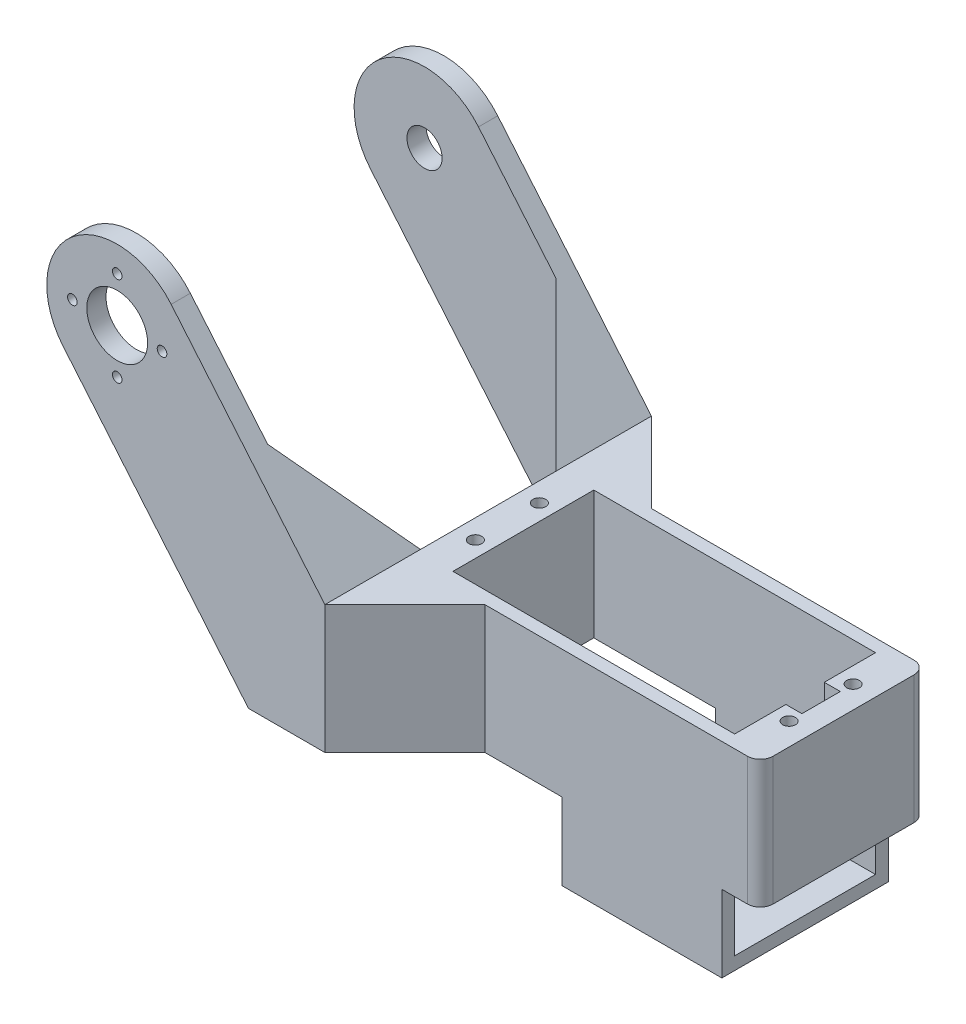
SolidWorks part; units mm, degrees
ref_plane "Alzado" through (0, 0, 0) normal (0, 0, 1) x (1, 0, 0)
ref_plane "Planta" through (0, 0, 0) normal (0, 1, 0) x (1, 0, 0)
ref_plane "Vista lateral" through (0, 0, 0) normal (1, 0, 0) x (0, 0, -1)
sketch "Croquis2" plane through (0, 0, 0) normal (0, 1, 0) x (1, 0, 0)
  line L0 (-30, 13) -> (-30, -13)
  line L1 (-22, 11) -> (22, 11)
  line L2 (-22, 11) -> (-22, -11)
  line L3 (-22, -11) -> (22, -11)
  line L4 (22, 11) -> (22, -11)
  line L5 (-22, 11) -> (22, -11) construction
  line L6 (-22, -11) -> (22, 11) construction
  line L7 (-30, -13) -> (28, -13)
  line L8 (28, 13) -> (28, -13)
  line L9 (-30, 13) -> (28, 13)
  point P0 (0, 0)
  point P10 (28, 0)
  point P11 (22, 0)
  dimension "D1" = 44
  dimension "D2" = 22
  dimension "D3" = 8
  dimension "D4" = 6
  dimension "D5" = 26
extrude "Saliente-Extruir3" add sketch "Croquis2" along normal blind 20
sketch "Croquis4" plane through (0, 20, 0) normal (0, 1, 0) x (1, 0, 0)
  line L14 (22, -11) -> (22, 11) construction
  line L15 (-22, 11) -> (-22, -11) construction
  line L16 (22, 3) -> (22, -3)
  line L17 (22, -3) -> (24.5, -3)
  line L18 (24.5, -3) -> (24.5, 3)
  line L19 (24.5, 3) -> (22, 3)
  circle A4 centre (-24.5, 5) radius 1
  circle A5 centre (-24.5, -5) radius 1
  circle A6 centre (24.5, -5) radius 1
  circle A7 centre (24.5, 5) radius 1
  point P9 (-22, 0)
  point P12 (22, 0)
  dimension "D2" = 2.5
  dimension "D1" = 2
  dimension "D3" = 10
  dimension "D4" = 2.5
  dimension "D5" = 5
  dimension "D6" = 6
  dimension "D7" = 2.5
extrude "Cut-Extrude1" cut sketch "Croquis4" against normal through all
sketch "Sketch1" plane through (-30, 0, 0) normal (-1, 0, 0) x (0, 0, 1)
  line L1 (25.5, 0) -> (-25.5, 0)
  line L2 (25.5, 0) -> (25.5, 20)
  line L3 (25.5, 20) -> (-25.5, 20)
  line L4 (-25.5, 0) -> (-25.5, 20)
  point P4 (0, 0)
  dimension "D1" = 51
extrude "Boss-Extrude1" add sketch "Sketch1" against normal blind 2.5
sketch "Croquis6" plane through (0, 0, 25.5) normal (0, 0, 1) x (1, 0, 0)
  line L0 (-27.5, 0) -> (-39.437, 0)
  line L1 (-39.437, 0) -> (-68.3624, 34.472)
  line L3 (-27.5, 20) -> (-51.5094, 48.6133)
  line L4 (-68.3624, 34.472) -> (-51.5094, 48.6133) construction
  circle A0 centre (-59.9359, 41.5427) radius 4.75
  arc A1 (-68.3624, 34.472) -> (-51.5094, 48.6133) centre (-59.9359, 41.5427) cw
  circle A3 centre (-52.9359, 41.5427) radius 0.75
  circle A4 centre (-59.9359, 34.5427) radius 0.75
  circle A5 centre (-66.9359, 41.5427) radius 0.75
  circle A6 centre (-59.9359, 48.5427) radius 0.75
  point P10 (-57.681, 41.4168)
  point P20 (-59.9359, 41.5427)
  dimension "D1" = 9.5
  dimension "D2" = 1.5
  dimension "D6" = 22
  dimension "D7" = 45
  dimension "D3" = 7
  dimension "D5" = 130
  dimension "D4" = 4
extrude "Saliente-Extruir5" add sketch "Croquis6" against normal blind 3
sketch "Sketch3" plane through (0, 0, -25.5) normal (0, 0, -1) x (-1, 0, 0)
  line L11 (51.5094, 48.6133) -> (27.5, 20)
  line L12 (27.5, 20) -> (30, 20)
  line L13 (30, 20) -> (30, 0)
  line L14 (30, 0) -> (39.437, 0)
  line L15 (39.437, 0) -> (68.3624, 34.472)
  line L16 (51.5094, 48.6133) -> (27.5, 20)
  line L17 (27.5, 20) -> (30, 20)
  line L18 (30, 20) -> (30, 0)
  line L19 (30, 0) -> (39.437, 0)
  line L20 (39.437, 0) -> (68.3624, 34.472)
  circle A3 centre (59.9359, 41.5427) radius 2.75
  arc A4 (68.3624, 34.472) -> (51.5094, 48.6133) centre (59.9359, 41.5427) ccw
  arc A9 (68.3624, 34.472) -> (51.5094, 48.6133) centre (59.9359, 41.5427) ccw
  dimension "D2" = 5.5
  dimension "D1" = 0
extrude "Boss-Extrude2" add sketch "Sketch3" against normal blind 3
sketch "Sketch5" plane through (22, 0, 0) normal (1, 0, 0) x (0, 0, -1)
  line L0 (-13, 0) -> (-13, -12)
  line L1 (-13, -12) -> (13, -12)
  line L2 (13, -12) -> (13, 0)
  line L3 (-11, 0) -> (-11, -10)
  line L4 (-11, -10) -> (11, -10)
  line L5 (11, -10) -> (11, 0)
  line L6 (-13, 0) -> (-11, 0)
  line L7 (13, 0) -> (11, 0)
  line L8 (-13, 0) -> (13, 0) construction
  dimension "D2" = 10
  dimension "D1" = 2
extrude "Boss-Extrude3" add sketch "Sketch5" against normal blind 25
fillet "Fillet1" radius 2 2 edges at (28, 10, -13) (28, 10, 13)
sketch "Sketch6" plane through (0, -12, 0) normal (0, -1, 0) x (1, 0, 0)
  circle A0 centre (10, 0) radius 2.15
  dimension "D3" = 4.3
extrude "Boss-Extrude4" add sketch "Sketch6" along normal blind 5
fillet "Fillet4" radius 1 1 edges at (10, -12, -2.15)
sketch "Sketch8" plane through (0, 20, 0) normal (0, 1, 0) x (1, 0, 0)
  line L0 (-27.5, 25.5) -> (-27.5, 13)
  line L1 (-27.5, 13) -> (-15, 13)
  line L2 (26, 13) -> (-27.5, 13) construction
  line L3 (-15, 13) -> (-27.5, 25.5)
  line L4 (-38.2485, 0) -> (38.2485, 0) construction
  line L5 (-27.5, -13) -> (-15, -13)
  line L6 (-27.5, -25.5) -> (-27.5, -13)
  line L7 (-15, -13) -> (-27.5, -25.5)
  point P12 (0, 0)
  point P13 (-25.5, 25.5)
  dimension "D1" = 45
extrude "Boss-Extrude5" add sketch "Sketch8" against normal up to surface (20 mm away) up to face at (24.5, 0, -6)
sketch "Sketch9" plane through (0, 0, 0) normal (0, -1, 0) x (1, 0, 0)
  line L0 (-39.437, 22.5) -> (-26.5, 9.563)
  line L2 (-26.5, 9.563) -> (-26.5, 22.5)
  line L3 (-26.5, 22.5) -> (-39.437, 22.5)
  line L4 (-27.5, 22.5) -> (-51.5094, 22.5) construction
  line L5 (-27.5, 22.5) -> (-30, 22.5) construction
  line L6 (38.2485, 0) -> (-38.2485, 0) construction
  line L7 (-26.5, -9.563) -> (-26.5, -22.5)
  line L8 (-39.437, -22.5) -> (-26.5, -9.563)
  line L9 (-26.5, -22.5) -> (-39.437, -22.5)
  point P3 (-25.5, 22.5)
  point P5 (0, 0)
  point P8 (-28, 22.5)
  point P9 (-28, 22.5)
  point P10 (0, 0)
  dimension "D1" = 45
extrude "Boss-Extrude6" add sketch "Sketch9" against normal up to surface (18.8082 mm away)
sketch "Sketch10" plane through (0, 20, 0) normal (0, 1, 0) x (1, 0, 0)
  line L0 (-30, 13.063) -> (-30, -13.063)
  line L1 (-30, -13.063) -> (-27.5, -10.563)
  line L2 (-30, 13.063) -> (-27.5, 10.563)
  line L3 (-27.5, 10.563) -> (-27.5, -10.563)
extrude "Cut-Extrude2" cut sketch "Sketch10" against normal through all
